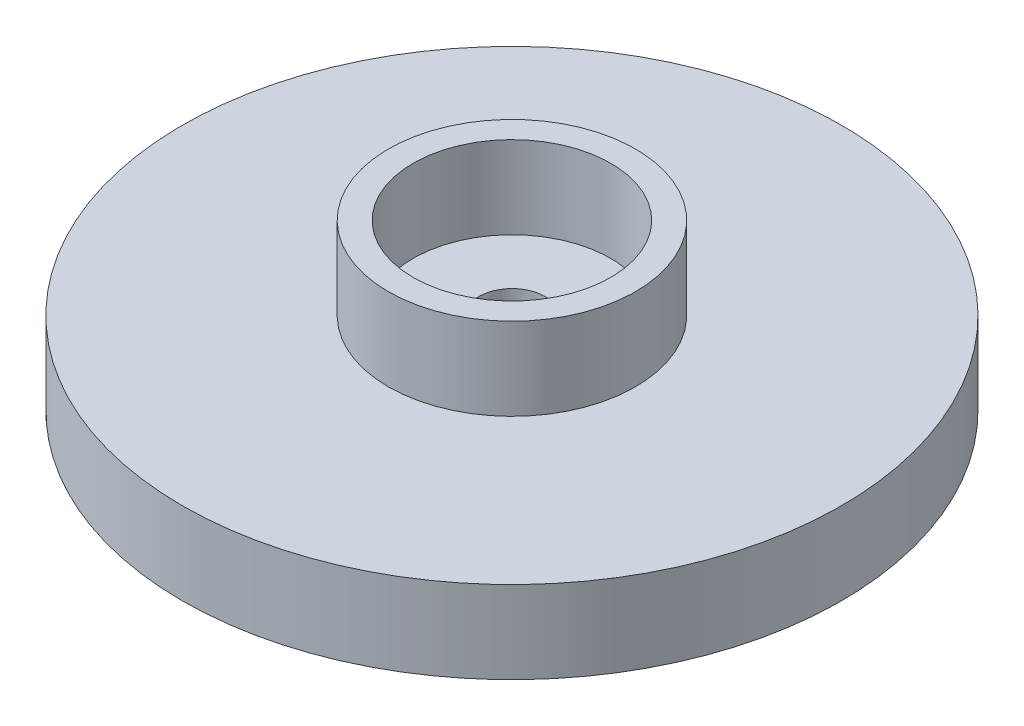
SolidWorks part; units mm, degrees
ref_plane "Front Plane" through (0, 0, 0) normal (0, 0, 1) x (1, 0, 0)
ref_plane "Top Plane" through (0, 0, 0) normal (0, 1, 0) x (1, 0, 0)
ref_plane "Right Plane" through (0, 0, 0) normal (1, 0, 0) x (0, 0, -1)
sketch "Sketch1" plane through (0, 0, 0) normal (0, 1, 0) x (1, 0, 0)
  circle A0 centre (0, 0) radius 10
extrude "Boss-Extrude1" add sketch "Sketch1" along normal blind 2.5
sketch "Sketch2" plane through (0, 2.5, 0) normal (0, 1, 0) x (1, 0, 0)
  circle A0 centre (0, 0) radius 3.75
  circle A1 centre (0, 0) radius 3
  circle A2 centre (0, 0) radius 1
extrude "Boss-Extrude2" add sketch "Sketch2" along normal blind 2.5 contours A0 A1
sketch "Sketch4" plane through (0, 2.5, 0) normal (0, 1, 0) x (1, 0, 0)
  circle A0 centre (0, 0) radius 1
extrude "Cut-Extrude1" cut sketch "Sketch4" against normal blind 2.5
